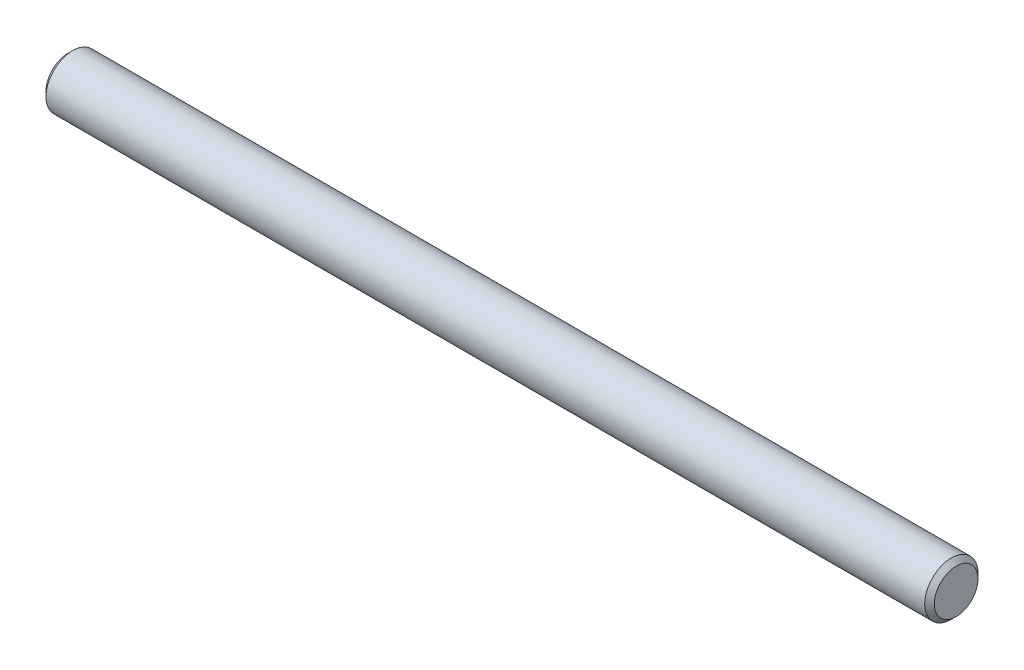
SolidWorks part; units mm, degrees
ref_plane "Front Plane" through (0, 0, 0) normal (0, 0, 1) x (1, 0, 0)
ref_plane "Top Plane" through (0, 0, 0) normal (0, 1, 0) x (1, 0, 0)
ref_plane "Right Plane" through (0, 0, 0) normal (1, 0, 0) x (0, 0, -1)
sketch "Sketch1" plane through (0, 0, 0) normal (0, 0, 1) x (1, 0, 0)
  line L0 (0, 0) -> (100, 0) construction
  line L1 (0, 0) -> (0, 2.46)
  line L2 (0, 2.46) -> (0.54, 3)
  line L3 (0.54, 3) -> (99.46, 3)
  line L4 (99.46, 3) -> (100, 2.46)
  line L5 (100, 2.46) -> (100, 0)
  line L6 (0, 0) -> (100, 0)
  dimension "FIX_1" = 45
  dimension "MSM_1" = 0.54
  dimension "M" = 6
  dimension "L" = 100
revolve "Revolve1" add sketch "Sketch1" angle 360 about L0
cosmetic thread "Thread201" parameters "ATD"=4.917
